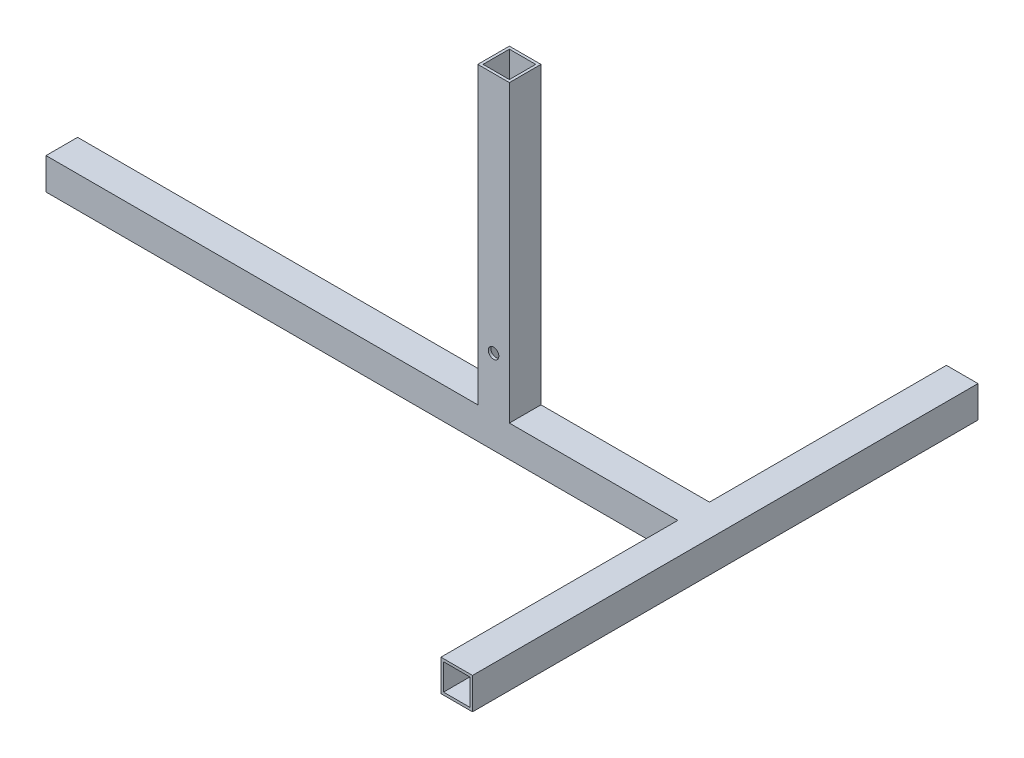
SolidWorks part; units mm, degrees
material "3003-O"
ref_plane "Front Plane" through (0, 0, 0) normal (0, 0, 1) x (1, 0, 0)
ref_plane "Top Plane" through (0, 0, 0) normal (0, 1, 0) x (1, 0, 0)
ref_plane "Right Plane" through (0, 0, 0) normal (1, 0, 0) x (0, 0, -1)
sketch "Sketch1" plane through (0, 0, 0) normal (1, 0, 0) x (0, 0, -1)
  line L0 (-15.875, 34.925) -> (15.875, 34.925)
  line L1 (-19.05, 0) -> (19.05, 0)
  line L2 (-19.05, 0) -> (-19.05, 38.1)
  line L3 (-19.05, 38.1) -> (19.05, 38.1)
  line L4 (19.05, 0) -> (19.05, 38.1)
  line L5 (15.875, 3.175) -> (15.875, 34.925)
  line L6 (-15.875, 3.175) -> (15.875, 3.175)
  line L7 (-15.875, 3.175) -> (-15.875, 34.925)
  point P4 (0, 0)
  dimension "D1" = 38.1
  dimension "D2" = 38.1
  dimension "D3" = 3.175
extrude "Boss-Extrude2" add sketch "Sketch1" along normal blind 222.25 and the other way blind 539.75
sketch "Sketch2" plane through (0, 38.1, 0) normal (0, 1, 0) x (1, 0, 0)
  line L0 (-539.75, -19.05) -> (222.25, -19.05) construction
  line L1 (-19.05, 19.05) -> (19.05, 19.05)
  line L2 (-19.05, 19.05) -> (-19.05, -19.05)
  line L3 (-19.05, -19.05) -> (19.05, -19.05)
  line L4 (19.05, 19.05) -> (19.05, -19.05)
  line L5 (-19.05, 19.05) -> (19.05, -19.05) construction
  line L6 (-19.05, -19.05) -> (19.05, 19.05) construction
  line L7 (-20.955, 0) -> (20.955, 0) construction
  line L8 (15.875, 15.875) -> (15.875, -15.875)
  line L9 (-15.875, -15.875) -> (15.875, -15.875)
  line L10 (-15.875, 15.875) -> (-15.875, -15.875)
  line L11 (-15.875, 15.875) -> (15.875, 15.875)
  point P0 (0, 0)
  dimension "D1" = 38.1
  dimension "D2" = 3.175
extrude "Boss-Extrude3" add sketch "Sketch2" along normal blind 355.6
sketch "Sketch3" plane through (0, 0, 0) normal (0, 0, 1) x (1, 0, 0)
  line L0 (19.05, 38.1) -> (222.25, 38.1) construction
  line L1 (222.25, 0) -> (260.35, 0)
  line L2 (222.25, 0) -> (222.25, 38.1)
  line L3 (222.25, 38.1) -> (260.35, 38.1)
  line L4 (260.35, 0) -> (260.35, 38.1)
  line L5 (225.425, 34.925) -> (257.175, 34.925)
  line L6 (257.175, 3.175) -> (257.175, 34.925)
  line L7 (225.425, 3.175) -> (257.175, 3.175)
  line L8 (225.425, 3.175) -> (225.425, 34.925)
  dimension "D1" = 38.1
  dimension "D2" = 3.175
extrude "Boss-Extrude4" add sketch "Sketch3" along normal mid plane 609.6
ref_plane "Plane1" through (0, 101.6, 0) normal (0, 1, 0) x (1, 0, 0)
sketch "Sketch4" plane through (0, 0, 19.05) normal (0, 0, 1) x (1, 0, 0)
  line L0 (335.28, 101.6) -> (-335.28, 101.6) construction
  line L1 (0, -223.52) -> (0, 223.52) construction
  circle A0 centre (0, 101.6) radius 6.35
  dimension "D1" = 12.7
extrude "Cut-Extrude1" cut sketch "Sketch4" against normal through all contours A0
